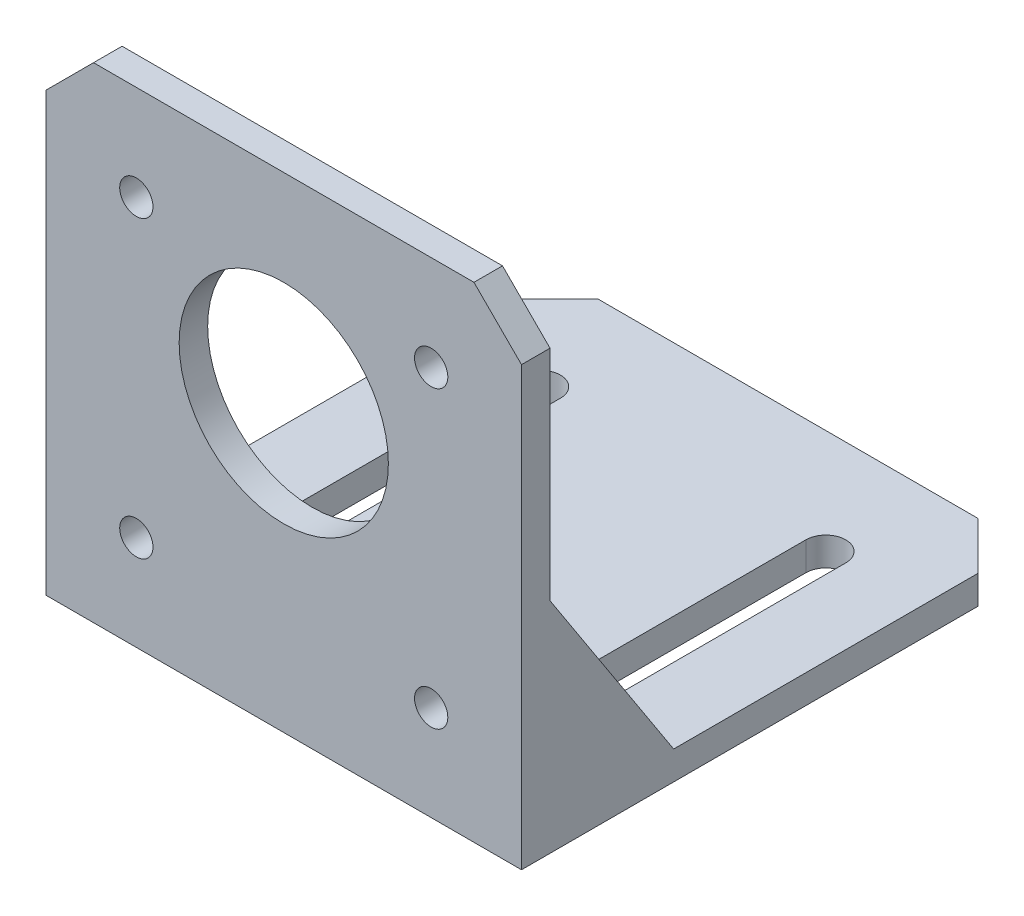
SolidWorks part; units mm, degrees
ref_plane "前视基准面" through (0, 0, 0) normal (0, 0, 1) x (1, 0, 0)
ref_plane "上视基准面" through (0, 0, 0) normal (0, 1, 0) x (1, 0, 0)
ref_plane "右视基准面" through (0, 0, 0) normal (1, 0, 0) x (0, 0, -1)
sketch "草图1" plane through (0, 0, 0) normal (0, 0, 1) x (1, 0, 0)
  line L0 (0, 25.5) -> (0, -25.5) construction
  line L1 (-25, 25.5) -> (25, 25.5)
  line L2 (-25, 25.5) -> (-25, -25.5)
  line L3 (-25, -25.5) -> (25, -25.5)
  line L4 (25, 25.5) -> (25, -25.5)
  line L5 (-25, 25.5) -> (25, -25.5) construction
  line L6 (-25, -25.5) -> (25, 25.5) construction
  line L7 (-25, 0) -> (25, 0) construction
  circle A0 centre (0, 4.5) radius 11
  circle A1 centre (-15.5, 15.5) radius 1.75
  circle A2 centre (-15.5, -15.5) radius 1.75
  circle A3 centre (15.5, -15.5) radius 1.75
  circle A4 centre (15.5, 15.5) radius 1.75
  point P0 (0, 0)
  dimension "D3" = 22
  dimension "D4" = 3.5
  dimension "D5" = 31
  dimension "D6" = 31
  dimension "D7" = 21
  dimension "D1" = 50
  dimension "D2" = 51
extrude "凸台-拉伸1" add sketch "草图1" along normal blind 3
chamfer "倒角1" distance 5 angle 45 2 edges at (-25, 25.5, 1.5) (25, 25.5, 1.5)
sketch "草图2" plane through (0, 0, 0) normal (0, 0, -1) x (-1, 0, 0)
  line L0 (-25, -25.5) -> (25, -25.5)
  line L1 (25, -25.5) -> (25, -22.5)
  line L2 (25, 20.5) -> (25, -25.5) construction
  line L3 (25, -22.5) -> (-25, -22.5)
  line L4 (-25, -25.5) -> (-25, 20.5) construction
  line L5 (-25, -22.5) -> (-25, -25.5)
  dimension "D1" = 3
extrude "凸台-拉伸2" add sketch "草图2" along normal blind 50
chamfer "倒角2" distance 5 angle 45 2 edges at (-25, -24, -50) (25, -24, -50)
sketch "草图3" plane through (0, -22.5, 0) normal (0, 1, 0) x (1, 0, 0)
  line L0 (0, 50) -> (0, 0) construction
  line L1 (-20, 50) -> (20, 50) construction
  line L2 (-15, 39) -> (-15, 9) construction
  line L3 (-17.1, 39) -> (-17.1, 9)
  line L4 (-12.9, 39) -> (-12.9, 9)
  line L5 (15, 39) -> (15, 9) construction
  line L6 (12.9, 39) -> (12.9, 9)
  line L7 (17.1, 39) -> (17.1, 9)
  arc A0 (-17.1, 39) -> (-12.9, 39) centre (-15, 39) cw
  arc A1 (-17.1, 9) -> (-12.9, 9) centre (-15, 9) ccw
  arc A2 (17.1, 9) -> (12.9, 9) centre (15, 9) cw
  arc A3 (17.1, 39) -> (12.9, 39) centre (15, 39) ccw
  dimension "D1" = 30
  dimension "D2" = 11
  dimension "D3" = 15
  dimension "D4" = 2.1
  dimension "D5" = 2.1
extrude "切除-拉伸1" cut sketch "草图3" against normal blind 50
sketch "草图4" plane through (25, 0, 0) normal (1, 0, 0) x (0, 0, -1)
  line L0 (0, -2.5) -> (13, -22.5)
  line L1 (0, -22.5) -> (0, 20.5) construction
  line L2 (13, -22.5) -> (0, -22.5)
  line L3 (0, -22.5) -> (0, -2.5)
  dimension "D1" = 20
  dimension "D2" = 13
extrude "凸台-拉伸3" add sketch "草图4" against normal blind 3
sketch "草图5" plane through (-25, 0, 0) normal (-1, 0, 0) x (0, 0, 1)
  line L3 (0, -22.5) -> (0, -2.5)
  line L4 (0, -2.5) -> (-13, -22.5)
  line L5 (-13, -22.5) -> (0, -22.5)
  line L6 (0, -22.5) -> (0, -2.5)
  line L7 (0, -2.5) -> (-13, -22.5)
  line L8 (-13, -22.5) -> (0, -22.5)
  dimension "D1" = 0
extrude "凸台-拉伸4" add sketch "草图5" against normal blind 3
